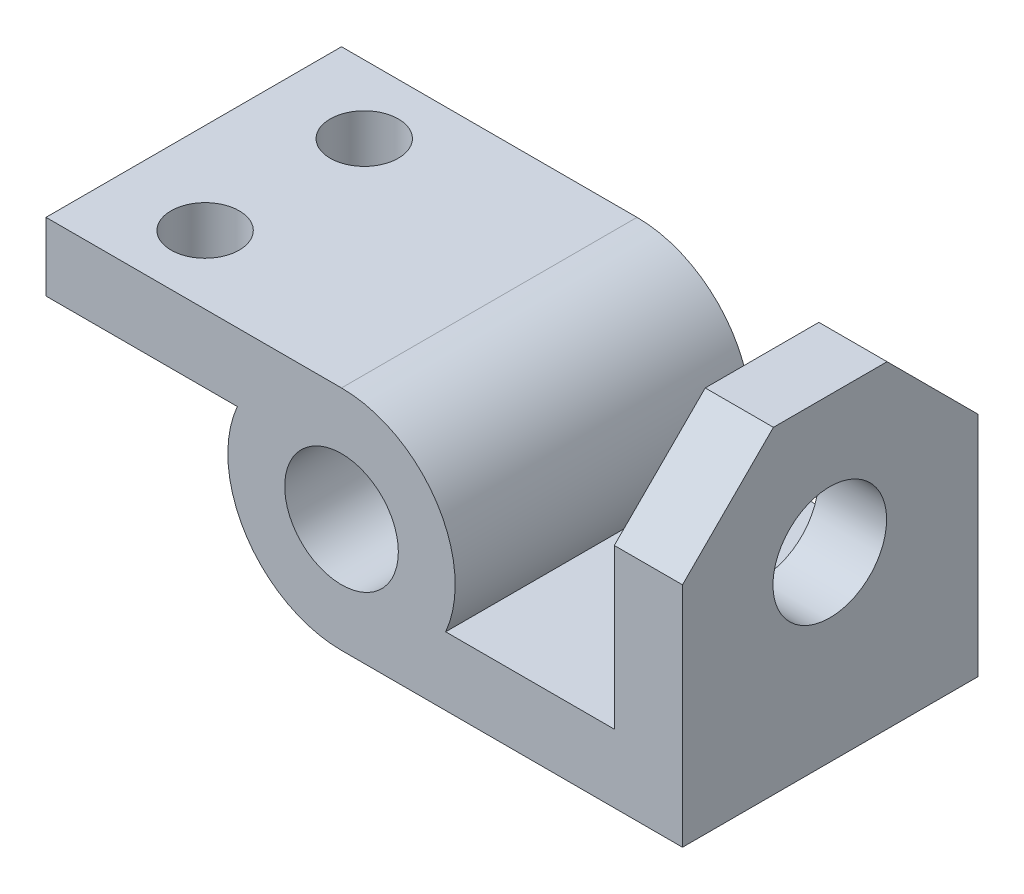
SolidWorks part; units mm, degrees
ref_plane "Front Plane" through (0, 0, 0) normal (0, 0, 1) x (1, 0, 0)
ref_plane "Top Plane" through (0, 0, 0) normal (0, 1, 0) x (1, 0, 0)
ref_plane "Right Plane" through (0, 0, 0) normal (1, 0, 0) x (0, 0, -1)
sketch "Sketch2" plane through (0, 0, 0) normal (0, 0, 1) x (1, 0, 0)
  line L0 (0, -31.75) -> (95.25, -31.75)
  line L1 (95.25, -31.75) -> (95.25, 57.15)
  line L2 (95.25, 57.15) -> (76.2, 57.15)
  line L3 (76.2, 57.15) -> (76.2, -12.7)
  line L4 (76.2, -12.7) -> (29.0994, -12.7)
  line L5 (0, 31.75) -> (-82.55, 31.75)
  line L6 (-82.55, 31.75) -> (-82.55, 12.7)
  line L7 (-82.55, 12.7) -> (-29.0994, 12.7)
  arc A0 (-29.0994, 12.7) -> (0, -31.75) centre (0, 0) ccw
  arc A1 (29.0994, -12.7) -> (0, 31.75) centre (0, 0) ccw
  circle A2 centre (0, 0) radius 15.875
  dimension "D1" = 31.75
  dimension "D8" = 31.75
  dimension "D2" = 19.05
  dimension "D3" = 82.55
  dimension "D4" = 88.9
  dimension "D5" = 19.05
  dimension "D6" = 95.25
  dimension "D7" = 19.05
extrude "Boss-Extrude1" add sketch "Sketch2" along normal blind 82.55
sketch "Sketch3" plane through (0, 31.75, 0) normal (0, 1, 0) x (1, 0, 0)
  line L0 (-82.55, -82.55) -> (-82.55, 0) construction
  line L1 (0, 0) -> (-82.55, 0) construction
  line L2 (0, -82.55) -> (-82.55, -82.55) construction
  circle A0 centre (-57.15, -63.5) radius 9.525
  circle A1 centre (-57.15, -19.05) radius 9.525
  point P8 (0, 0)
  dimension "D1" = 19.05
  dimension "D2" = 19.05
  dimension "D3" = 25.4
  dimension "D4" = 19.05
  dimension "D5" = 19.05
extrude "Cut-Extrude1" cut sketch "Sketch3" against normal blind 19.05
chamfer "Chamfer1" distance 25.4 distance2 25.4 2 edges at (85.725, 57.15, 0) (85.725, 57.15, 82.55)
sketch "Sketch4" plane through (95.25, 0, 0) normal (1, 0, 0) x (0, 0, -1)
  line L0 (0, -31.75) -> (0, 31.75) construction
  line L1 (-82.55, -31.75) -> (0, -31.75) construction
  circle A0 centre (-41.402, 19.05) radius 15.875
  dimension "D1" = 31.75
  dimension "D2" = 41.402
  dimension "D3" = 50.8
extrude "Cut-Extrude2" cut sketch "Sketch4" against normal blind 19.05
